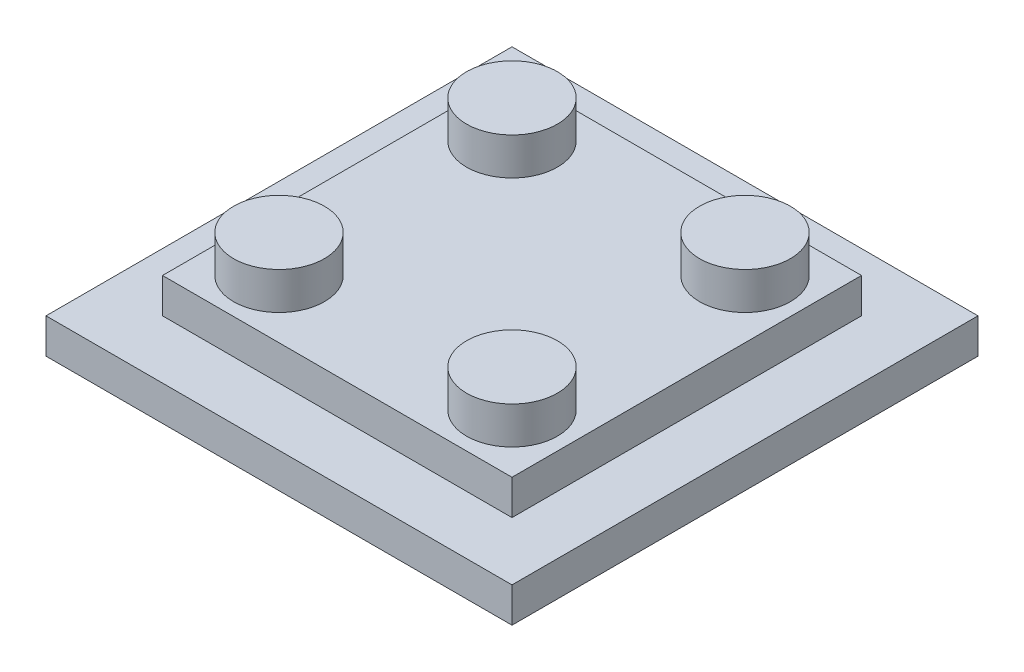
SolidWorks part; units mm, degrees
ref_plane "Front Plane" through (0, 0, 0) normal (0, 0, 1) x (1, 0, 0)
ref_plane "Top Plane" through (0, 0, 0) normal (0, 1, 0) x (1, 0, 0)
ref_plane "Right Plane" through (0, 0, 0) normal (1, 0, 0) x (0, 0, -1)
sketch "Sketch1" plane through (0, 0, 0) normal (0, 1, 0) x (1, 0, 0)
  line L1 (-15, 15) -> (15, 15)
  line L2 (-15, 15) -> (-15, -15)
  line L3 (-15, -15) -> (15, -15)
  line L4 (15, 15) -> (15, -15)
  line L5 (-15, 15) -> (15, -15) construction
  line L6 (-15, -15) -> (15, 15) construction
  line L7 (-10, 10) -> (10, 10) construction
  line L8 (-10, 10) -> (-10, -10) construction
  line L9 (-10, -10) -> (10, -10) construction
  line L10 (10, 10) -> (10, -10) construction
  line L11 (-10, 10) -> (10, -10) construction
  line L12 (-10, -10) -> (10, 10) construction
  circle A0 centre (-10, 10) radius 3.9
  circle A1 centre (10, 10) radius 3.9
  circle A2 centre (-10, -10) radius 3.9
  circle A3 centre (10, -10) radius 3.9
  point P0 (0, 0)
  point P6 (0, 0)
  dimension "D5" = 7.8
  dimension "D6" = 7.8
  dimension "D7" = 7.8
  dimension "D8" = 7.8
  dimension "D1" = 30
  dimension "D2" = 30
  dimension "D3" = 20
  dimension "D4" = 20
extrude "Boss-Extrude1" add sketch "Sketch1" along normal blind 3 contours L4 L1 L2 L3 A3 A2 A1 A0 | A0 | A1 | A2 | A3
sketch "Sketch2" plane through (0, 3, 0) normal (0, 1, 0) x (1, 0, 0)
  circle A0 centre (-10, -10) radius 3.9 construction
  circle A1 centre (10, -10) radius 3.9 construction
  circle A2 centre (10, 10) radius 3.9 construction
  circle A3 centre (-10, 10) radius 3.9 construction
  circle A4 centre (-10, -10) radius 3.9
  circle A5 centre (10, -10) radius 3.9
  circle A6 centre (10, 10) radius 3.9
  circle A7 centre (-10, 10) radius 3.9
extrude "Boss-Extrude2" add sketch "Sketch2" along normal blind 3.2
sketch "Sketch3" plane through (0, 0, 0) normal (0, -1, 0) x (1, 0, 0)
  line L1 (-20, 20) -> (20, 20)
  line L2 (-20, 20) -> (-20, -20)
  line L3 (-20, -20) -> (20, -20)
  line L4 (20, 20) -> (20, -20)
  line L5 (-20, 20) -> (20, -20) construction
  line L6 (-20, -20) -> (20, 20) construction
  point P0 (0, 0)
  dimension "D1" = 40
  dimension "D2" = 40
extrude "Boss-Extrude3" add sketch "Sketch3" along normal blind 3
